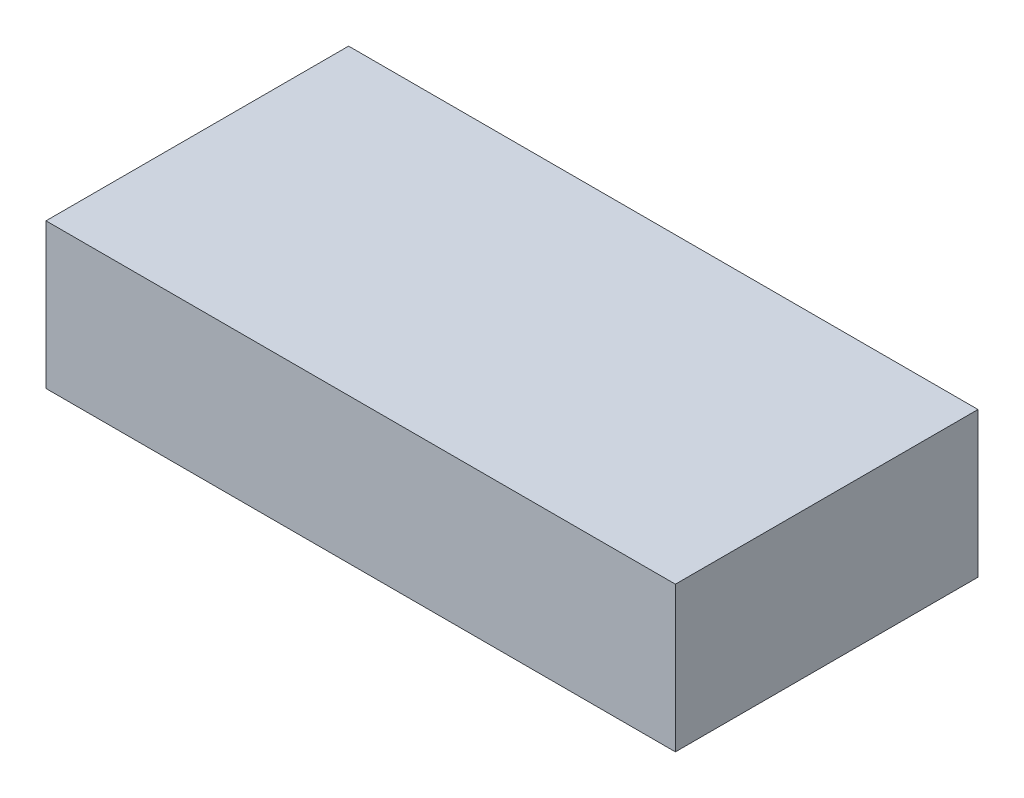
SolidWorks part; units mm, degrees
ref_plane "Front Plane" through (0, 0, 0) normal (0, 0, 1) x (1, 0, 0)
ref_plane "Top Plane" through (0, 0, 0) normal (0, 1, 0) x (1, 0, 0)
ref_plane "Right Plane" through (0, 0, 0) normal (1, 0, 0) x (0, 0, -1)
sketch "Sketch1" plane through (0, 0, 0) normal (0, 1, 0) x (1, 0, 0)
  line L1 (-26, -12.5) -> (26, -12.5)
  line L2 (-26, -12.5) -> (-26, 12.5)
  line L3 (-26, 12.5) -> (26, 12.5)
  line L4 (26, -12.5) -> (26, 12.5)
  line L5 (-26, -12.5) -> (26, 12.5) construction
  line L6 (-26, 12.5) -> (26, -12.5) construction
  point P0 (0, 0)
  dimension "D1" = 52
  dimension "D2" = 25
extrude "Boss-Extrude1" add sketch "Sketch1" along normal blind 12
